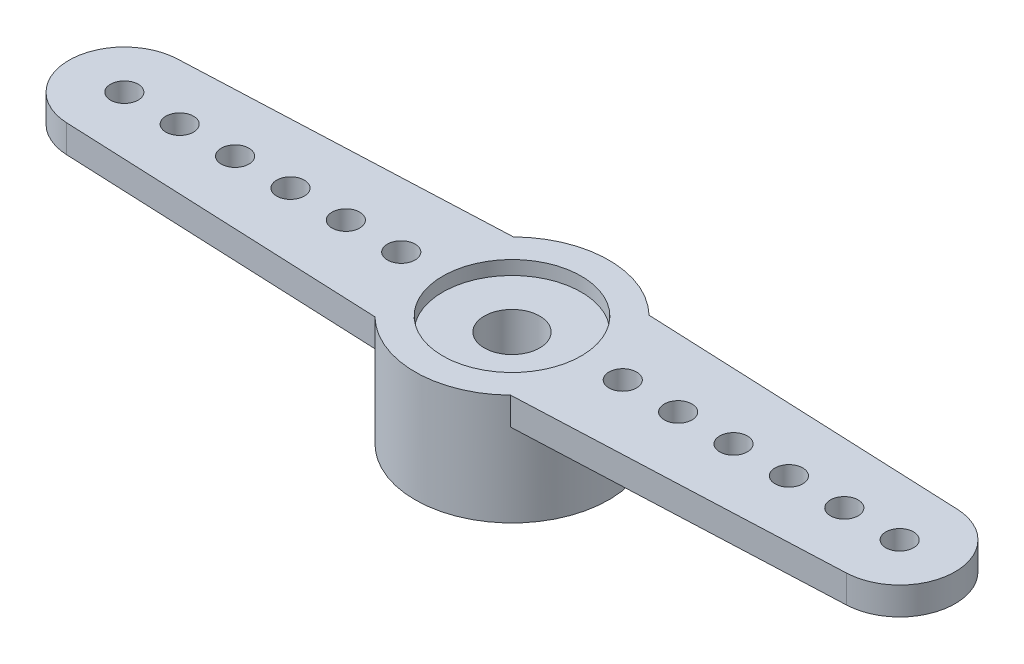
SolidWorks part; units mm, degrees
ref_plane "Front Plane" through (0, 0, 0) normal (0, 0, 1) x (1, 0, 0)
ref_plane "Top Plane" through (0, 0, 0) normal (0, 1, 0) x (1, 0, 0)
ref_plane "Right Plane" through (0, 0, 0) normal (1, 0, 0) x (0, 0, -1)
sketch "Sketch1" plane through (0, 0, 0) normal (0, 1, 0) x (1, 0, 0)
  circle A0 centre (0, 0) radius 3.5
  circle A1 centre (0, 0) radius 2.5
  dimension "D1" = 7
  dimension "D2" = 1
extrude "Boss-Extrude1" add sketch "Sketch1" along normal blind 4
sketch "Sketch2" plane through (0, 4, 0) normal (0, 1, 0) x (1, 0, 0)
  circle A0 centre (0, 0) radius 1
  circle A1 centre (0, 0) radius 3.5
  circle A2 centre (0, 0) radius 3.5 construction
  dimension "D1" = 2
extrude "Boss-Extrude2" add sketch "Sketch2" against normal blind 1.5 from offset 0.5 offset against normal yes
sketch "Sketch3" plane through (0, 4, 0) normal (0, 1, 0) x (1, 0, 0)
  line L0 (-14, 0) -> (14, 0) construction
  line L1 (-2.4495, 2.5) -> (-14.0862, 1.9981)
  line L2 (-14.0862, -1.9981) -> (-2.4495, -2.5)
  line L3 (-16, 0) -> (-16, -1.6123) construction
  line L4 (0, -2.2) -> (0, 2.2) construction
  line L5 (14.0862, -1.9981) -> (2.4495, -2.5)
  line L6 (2.4495, 2.5) -> (14.0862, 1.9981)
  circle A0 centre (0, 0) radius 3.5 construction
  circle A1 centre (-14, 0) radius 2 construction
  arc A2 (-14.0862, 1.9981) -> (-14.0862, -1.9981) centre (-14, 0) ccw
  arc A3 (14.0862, 1.9981) -> (14.0862, -1.9981) centre (14, 0) cw
  circle A4 centre (0, 0) radius 3.5 construction
  arc A6 (-2.4495, 2.5) -> (-2.4495, -2.5) centre (0, 0) ccw
  arc A7 (2.4495, 2.5) -> (2.4495, -2.5) centre (0, 0) cw
  point P5 (0, 0)
  circle M5 centre (0, 0) radius 3.5
  dimension "D1" = 16
  dimension "D2" = 4
  dimension "D3" = 5
extrude "Boss-Extrude3" add sketch "Sketch3" against normal blind 1 contours L1 A2 L2 M5 | A3 L6 L5 M5
sketch "Sketch4" plane through (0, 4, 0) normal (0, 1, 0) x (1, 0, 0)
  line L0 (-18.8971, 0) -> (18.8971, 0) construction
  line L1 (0, -2.2) -> (0, 2.2) construction
  circle A0 centre (4, 0) radius 0.5
  circle A1 centre (6, 0) radius 0.5
  circle A2 centre (8, 0) radius 0.5
  circle A3 centre (10, 0) radius 0.5
  circle A4 centre (12, 0) radius 0.5
  circle A5 centre (14, 0) radius 0.5
  circle A6 centre (-14, 0) radius 0.5
  circle A7 centre (-12, 0) radius 0.5
  circle A8 centre (-10, 0) radius 0.5
  circle A9 centre (-8, 0) radius 0.5
  circle A10 centre (-6, 0) radius 0.5
  circle A11 centre (-4, 0) radius 0.5
  point P3 (0, 0)
  point P4 (0, 0)
  point P8 (0, 0)
  dimension "D1" = 4
  dimension "D2" = 1
  dimension "D4" = 10
  dimension "D3" = 6
extrude "Cut-Extrude1" cut sketch "Sketch4" against normal up to next
